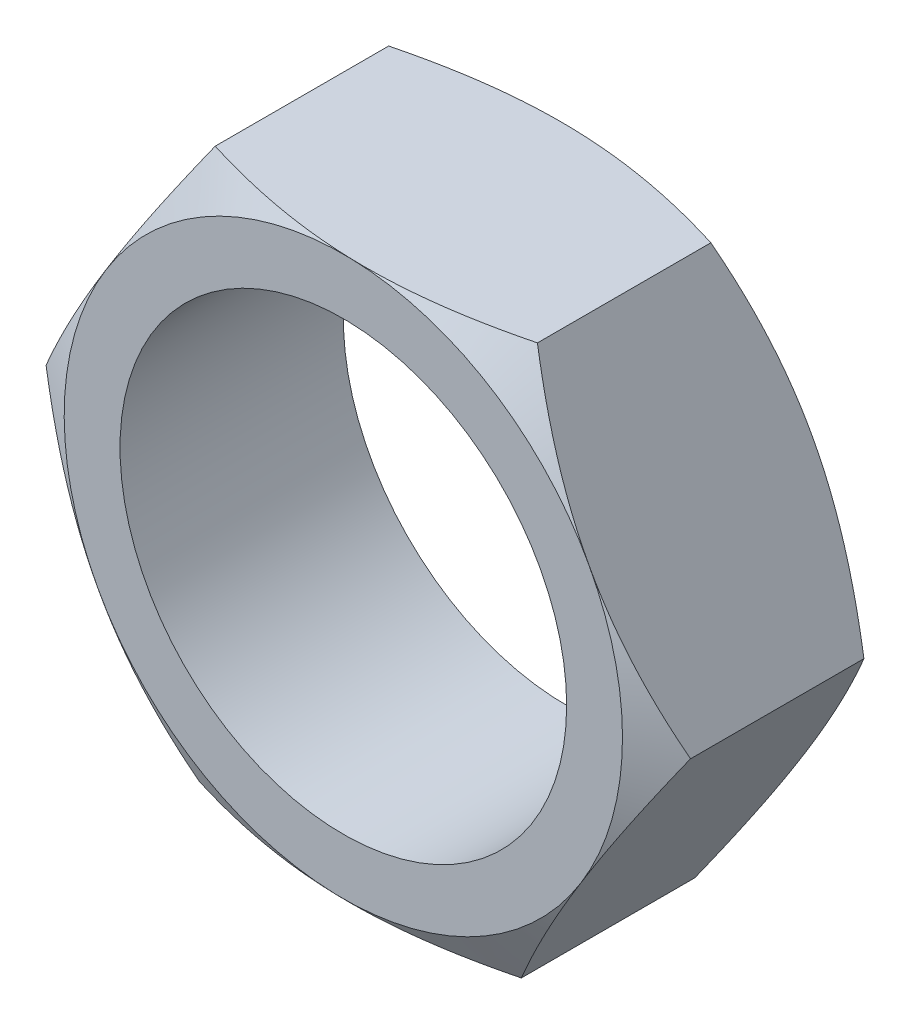
SolidWorks part; units mm, degrees
material "Cast Alloy Steel"
ref_plane "Front Plane" through (0, 0, 0) normal (0, 0, 1) x (1, 0, 0)
ref_plane "Top Plane" through (0, 0, 0) normal (0, 1, 0) x (1, 0, 0)
ref_plane "Right Plane" through (0, 0, 0) normal (1, 0, 0) x (0, 0, -1)
sketch "Sketch1" plane through (0, 0, 0) normal (0, 0, 1) x (1, 0, 0)
  line L1 (3.787, 6.1434) -> (-3.4268, 6.3514)
  line L2 (-3.4268, 6.3514) -> (-7.2139, 0.208)
  line L3 (-7.2139, 0.208) -> (-3.787, -6.1434)
  line L4 (-3.787, -6.1434) -> (3.4268, -6.3514)
  line L5 (3.4268, -6.3514) -> (7.2139, -0.208)
  line L6 (7.2139, -0.208) -> (3.787, 6.1434)
  circle A0 centre (0, 0) radius 5
  circle A1 centre (0, 0) radius 6.25 construction
  dimension "D1" = 10
  dimension "D2" = 12.5
extrude "Boss-Extrude1" add sketch "Sketch1" along normal blind 5
sketch "Sketch2" plane through (0, 0, 5) normal (0, 0, 1) x (1, 0, 0)
  circle A0 centre (0, 0) radius 6.25
  dimension "D1" = 12.5
extrude "Cut-Extrude1" cut sketch "Sketch2" against normal through all draft 60 flip side to cut
sketch "Sketch3" plane through (0, 0, 0) normal (0, 0, -1) x (-1, 0, 0)
  circle A0 centre (0, 0) radius 6.25
  dimension "D1" = 12.5
extrude "Cut-Extrude2" cut sketch "Sketch3" against normal through all draft 60 flip side to cut
